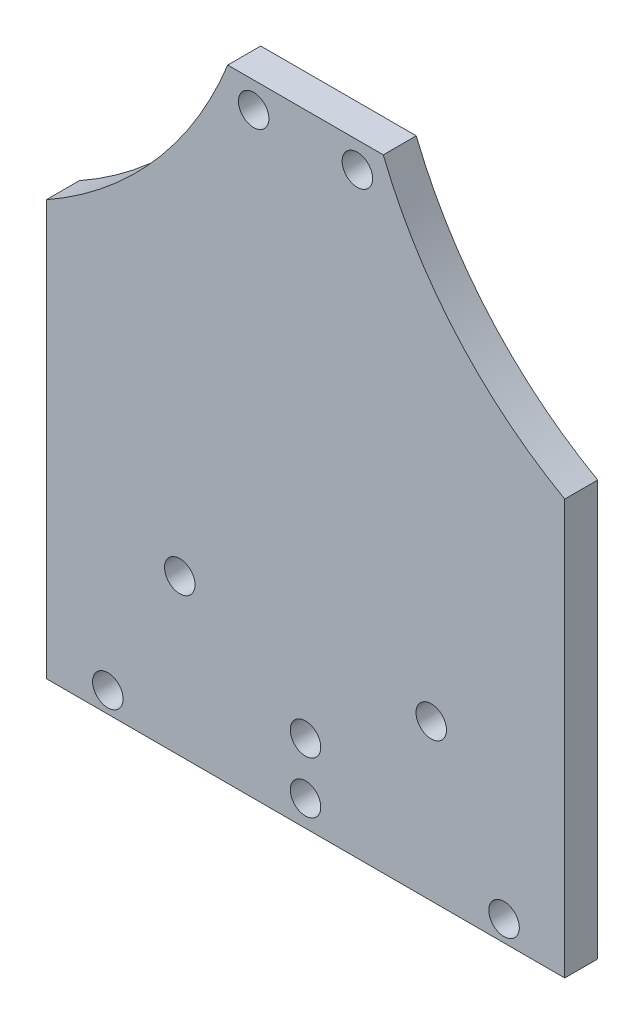
SolidWorks part; units mm, degrees
ref_plane "Front Plane" through (0, 0, 0) normal (0, 0, 1) x (1, 0, 0)
ref_plane "Top Plane" through (0, 0, 0) normal (0, 1, 0) x (1, 0, 0)
ref_plane "Right Plane" through (0, 0, 0) normal (1, 0, 0) x (0, 0, -1)
sketch "Sketch1" plane through (0, 0, 0) normal (0, 0, 1) x (1, 0, 0)
  line L0 (0, 0) -> (0, -36.2959) construction
  line L1 (-25, 20) -> (25, 20)
  line L2 (-25, 20) -> (-25, -10)
  line L3 (-25, -10) -> (25, -10)
  line L4 (25, 20) -> (25, -10)
  circle A2 centre (-12.125, 5) radius 1.47
  circle A3 centre (12.125, 5) radius 1.47
  dimension "D3" = 2.94
  dimension "D4" = 12.125
  dimension "D5" = 15
  dimension "D1" = 50
  dimension "D2" = 30
extrude "Boss-Extrude1" add sketch "Sketch1" along normal blind 3.18
sketch "Sketch2" plane through (0, 0, 0) normal (0, 0, -1) x (-1, 0, 0)
  line L0 (-25, 20) -> (25, 20) construction
  line L1 (-25, 20) -> (25, 20)
  line L2 (-25, 20) -> (-25, 30)
  line L4 (25, 20) -> (25, 30)
  line L7 (0, 0) -> (0, 50) construction
  line L8 (-7.5, 50) -> (7.5, 50)
  arc A0 (-25, 30) -> (-7.5, 50) centre (-44.6436, 64.8444) ccw
  arc A1 (25, 30) -> (7.5, 50) centre (44.6436, 64.8444) cw
  dimension "D6" = 40
  dimension "D1" = 10
  dimension "D2" = 50
  dimension "D4" = 7.5
  dimension "D5" = 30
extrude "Boss-Extrude2" add sketch "Sketch2" against normal blind 3.18
sketch "Sketch3" plane through (0, 0, 0) normal (0, 0, -1) x (-1, 0, 0)
  line L0 (0, 0) -> (0, 69.8512) construction
  line L1 (7.5, 50) -> (-7.5, 50) construction
  circle A0 centre (-5, 47.5) radius 1.47
  circle A1 centre (5, 47.5) radius 1.47
  dimension "D1" = 2.94
  dimension "D2" = 2.5
  dimension "D3" = 5
extrude "Cut-Extrude1" cut sketch "Sketch3" against normal through all
sketch "Sketch4" plane through (0, 0, 0) normal (0, 0, -1) x (-1, 0, 0)
  line L0 (-19.1461, -11) -> (-19.1461, -58) construction
  line L1 (-17.5561, -11) -> (-20.7361, -11) construction
  line L2 (-17.5561, -58) -> (-20.7361, -58) construction
  line L3 (0, -11) -> (0, -99.97) construction
  line L4 (-1.59, -11) -> (1.59, -11) construction
  line L5 (-1.59, -99.97) -> (1.59, -99.97) construction
  line L6 (19.0639, -11) -> (19.0639, -54.53) construction
  line L7 (20.6539, -11) -> (17.4739, -11) construction
  line L8 (20.6539, -54.53) -> (17.4739, -54.53) construction
  line L12 (25, -10) -> (-25, -10) construction
  line L13 (0, 0) -> (0, -10) construction
  line L14 (3.09, 0) -> (-3.09, 0) construction
  circle A1 centre (0, -7.5) radius 1.47
  circle A4 centre (-19.1461, -8) radius 1.47
  circle A5 centre (0, -2.5) radius 1.47
  circle A6 centre (19.0639, -8) radius 1.47
  dimension "D1" = 2
  dimension "D2" = 2.94
  dimension "D3" = 2.5
  dimension "D5" = 2.5
  dimension "D4" = 2.94
  dimension "D6" = 2.94
  dimension "D7" = 2
extrude "Cut-Extrude2" cut sketch "Sketch4" against normal through all
